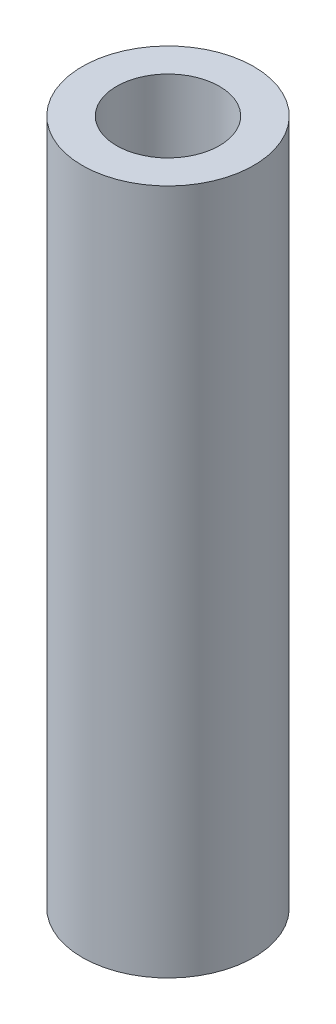
SolidWorks part; units mm, degrees
ref_plane "Front Plane" through (0, 0, 0) normal (0, 0, 1) x (1, 0, 0)
ref_plane "Top Plane" through (0, 0, 0) normal (0, 1, 0) x (1, 0, 0)
ref_plane "Right Plane" through (0, 0, 0) normal (1, 0, 0) x (0, 0, -1)
sketch "Sketch1" plane through (0, 0, 0) normal (0, 1, 0) x (1, 0, 0)
  circle A0 centre (0, 0) radius 2.5
  circle A1 centre (0, 0) radius 1.5
  dimension "D1" = 5
  dimension "D2" = 3
extrude "Boss-Extrude1" add sketch "Sketch1" along normal mid plane 20
move or copy body "Body-Move/Copy1" bodies to move or copy 101
